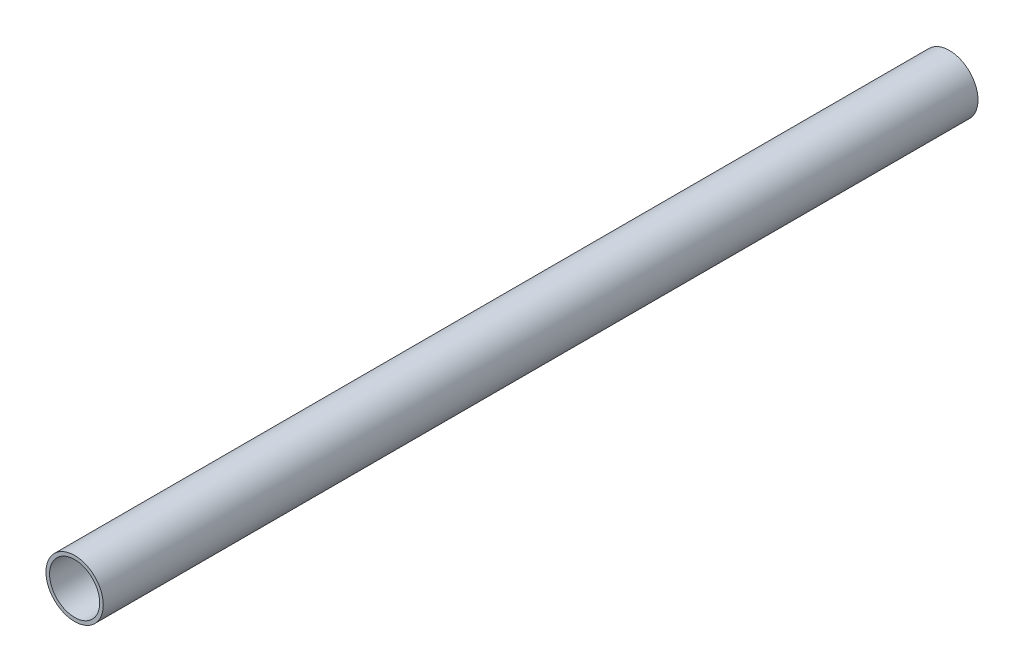
SolidWorks part; units mm, degrees
material "PC High Viscosity"
ref_plane "Front Plane" through (0, 0, 0) normal (0, 0, 1) x (1, 0, 0)
ref_plane "Top Plane" through (0, 0, 0) normal (0, 1, 0) x (1, 0, 0)
ref_plane "Right Plane" through (0, 0, 0) normal (1, 0, 0) x (0, 0, -1)
sketch "Sketch1" plane through (0, 0, 0) normal (0, 0, 1) x (1, 0, 0)
  circle A0 centre (0, 0) radius 12.7
  circle A1 centre (0, 0) radius 11.1125
  dimension "D1" = 25.4
  dimension "D2" = 1.5875
extrude "Boss-Extrude1" add sketch "Sketch1" along normal blind 387.62
